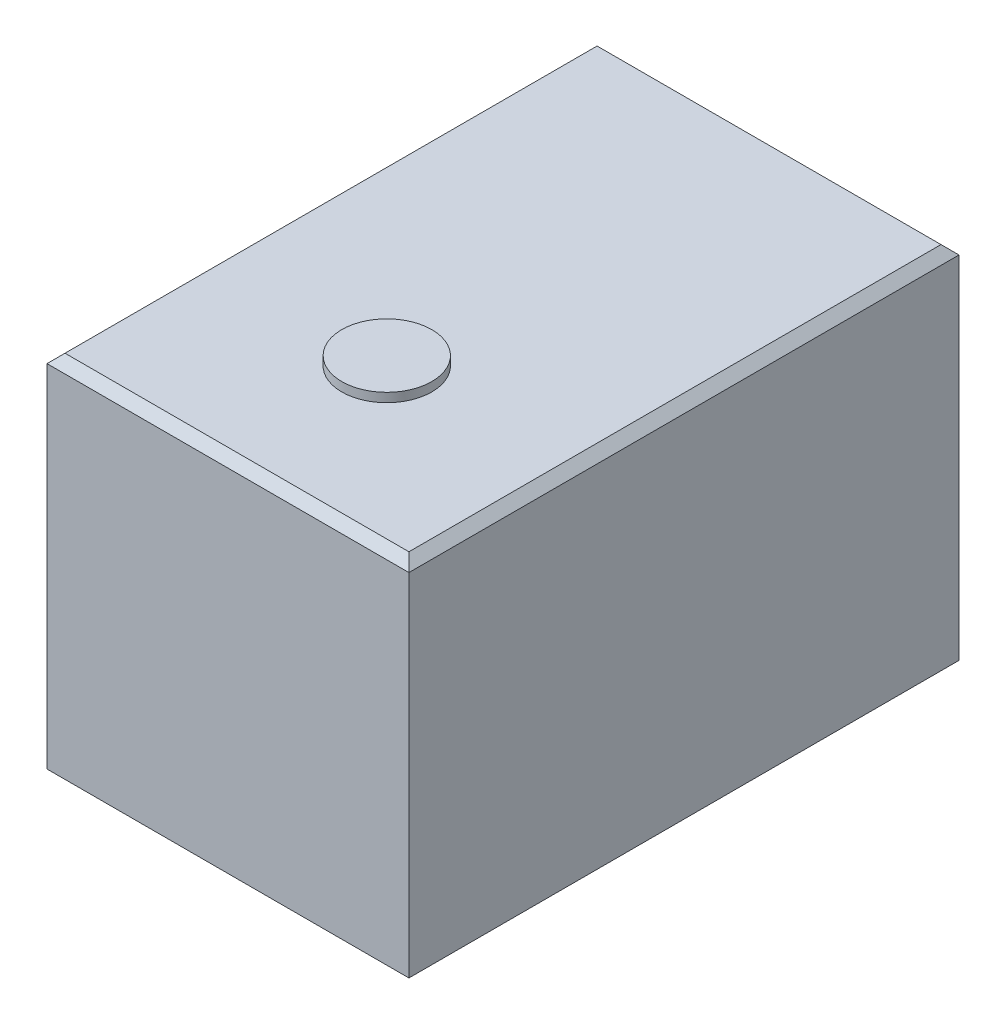
SolidWorks part; units mm, degrees
ref_plane "Front Plane" through (0, 0, 0) normal (0, 0, 1) x (1, 0, 0)
ref_plane "Top Plane" through (0, 0, 0) normal (0, 1, 0) x (1, 0, 0)
ref_plane "Right Plane" through (0, 0, 0) normal (1, 0, 0) x (0, 0, -1)
sketch "Sketch1" plane through (0, 0, 0) normal (0, 1, 0) x (1, 0, 0)
  line L0 (0, 0) -> (40.2, 0)
  line L1 (40.2, 0) -> (40.2, 61.1)
  line L2 (40.2, 61.1) -> (0, 61.1)
  line L3 (0, 61.1) -> (0, 0)
extrude "Boss-Extrude1" add sketch "Sketch1" along normal blind 41
chamfer "Chamfer1" distance 1 angle 45 4 edges at (20.1, 41, -61.1) (40.2, 41, -30.55) (20.1, 41, 0) (0, 41, -30.55)
chamfer "Chamfer2" distance 1 angle 45 4 edges at (20.1, 0, 0) (40.2, 0, -30.55) (20.1, 0, -61.1) (0, 0, -30.55)
sketch "Sketch2" plane through (0, 0, 0) normal (0, -1, 0) x (1, 0, 0)
  circle A0 centre (20.1, -17.641) radius 5
extrude "Boss-Extrude2" add sketch "Sketch2" along normal blind 1
ref_plane "Plane1" through (0, 20.5, 0) normal (0, 1, 0) x (1, 0, 0)
mirror "Mirror1" about plane through (0, 20.5, 0) normal (0, 1, 0) of "Boss-Extrude2"
